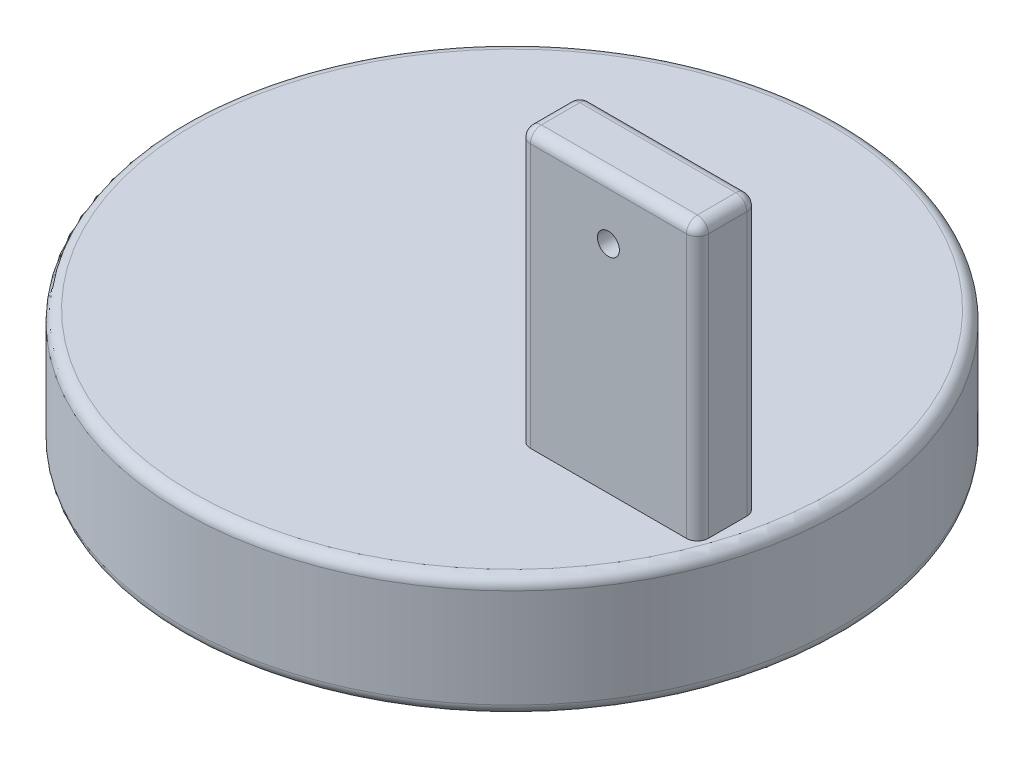
SolidWorks part; units mm, degrees
ref_plane "前视基准面" through (0, 0, 0) normal (0, 0, 1) x (1, 0, 0)
ref_plane "上视基准面" through (0, 0, 0) normal (0, 1, 0) x (1, 0, 0)
ref_plane "右视基准面" through (0, 0, 0) normal (1, 0, 0) x (0, 0, -1)
other "Configuration Table"
sketch "草图2" plane through (0, 0, 0) normal (0, 1, 0) x (1, 0, 0)
  circle A0 centre (0, 0) radius 30
  dimension "D1" = 60
extrude "凸台-拉伸1" add sketch "草图2" along normal blind 11
ref_plane "基准面1" through (0, 0, 4.63) normal (0, 0, 1) x (1, 0, 0)
sketch "草图3" plane through (0, 0, 4.63) normal (0, 0, 1) x (1, 0, 0)
  line L0 (27, 11) -> (27, 36)
  line L1 (30, 11) -> (-30, 11) construction
  line L2 (27, 36) -> (10.8, 36)
  line L3 (10.8, 36) -> (10.8, 11)
  line L4 (30, 0) -> (30, 11) construction
  line L5 (18.9, 54.6324) -> (18.9, 6.7076) construction
  line L6 (27, 11) -> (10.8, 11)
  circle A0 centre (18.9, 30.67) radius 1
  dimension "D2" = 19.67
  dimension "D5" = 2
  dimension "D1" = 25
  dimension "D3" = 3
  dimension "D4" = 16.2
extrude "凸台-拉伸2" add sketch "草图3" along normal blind 5.5
fillet "圆角1" radius 1 10 edges at (10.8, 23.5, 4.63) (27, 23.5, 4.63) (10.8, 23.5, 10.13) (27, 23.5, 10.13) (18.9, 36, 4.63) (18.9, 36, 10.13) (10.8, 36, 7.38) (27, 36, 7.38) (0, 0, 30) (0, 11, 30)
sketch "草图4" plane through (0, 0, 0) normal (0, -1, 0) x (-1, 0, 0)
  line L0 (0, -32.3517) -> (0, 32.2558) construction
  line L1 (36.4047, 0) -> (-38.2753, 0) construction
  circle A0 centre (0, -13) radius 1.3
  circle A1 centre (-13, 0) radius 1.3
  circle A2 centre (0, 13) radius 1.3
  circle A3 centre (13, 0) radius 1.3
  point P15 (0, 0)
  dimension "D1" = 2.6
  dimension "D2" = 13
  dimension "D3" = 4
extrude "切除-拉伸1" cut sketch "草图4" against normal blind 5
